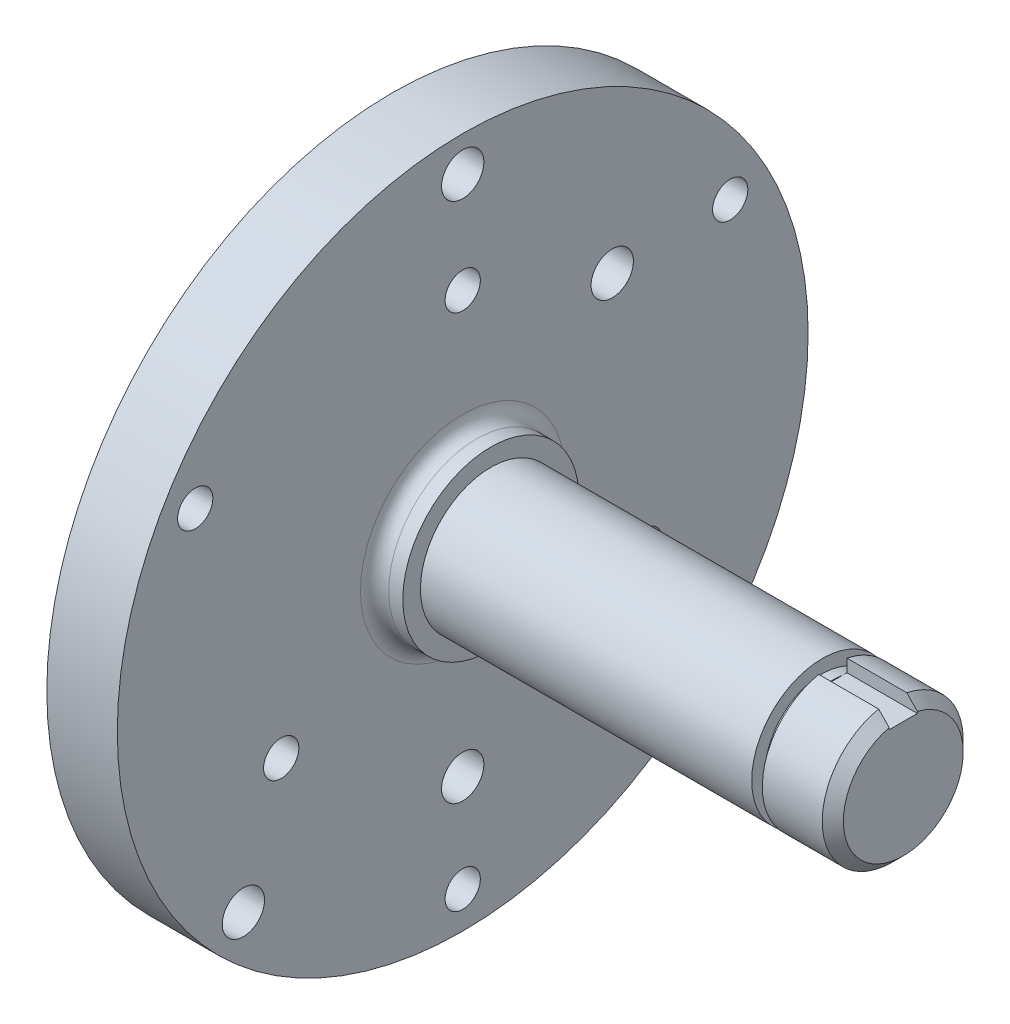
SolidWorks part; units mm, degrees
ref_plane "Plan de face" through (0, 0, 0) normal (0, 0, 1) x (1, 0, 0)
ref_plane "Plan de dessus" through (0, 0, 0) normal (0, 1, 0) x (1, 0, 0)
ref_plane "Plan de droite" through (0, 0, 0) normal (1, 0, 0) x (0, 0, -1)
sketch "Esquisse1" plane through (0, 0, 0) normal (0, 0, 1) x (1, 0, 0)
  line L0 (-18.2864, 0) -> (63.7946, 0) construction
  line L1 (-14, 0) -> (-14, 49)
  line L2 (-14, 49) -> (-4, 49)
  line L3 (-4, 49) -> (-4, 14.5)
  line L4 (-2, 12.5) -> (0, 12.5)
  line L5 (0, 12.5) -> (0, 10)
  line L6 (0, 10) -> (47, 10)
  line L7 (47, 10) -> (47, 8.1277)
  line L8 (47, 8.1277) -> (48.5, 8.1277)
  line L9 (48.5, 8.1277) -> (48.5, 10)
  line L10 (48.5, 10) -> (57, 10)
  line L11 (58.5, 8.5) -> (58.5, 0)
  line L12 (57, 10) -> (58.5, 8.5)
  line L13 (-14, 0) -> (58.5, 0)
  arc A0 (-4, 14.5) -> (-2, 12.5) centre (-2, 14.5) ccw
  point P14 (58.5, 10)
  dimension "D9" = 2
  dimension "D1" = 98
  dimension "D2" = 25
  dimension "D3" = 20
  dimension "D4" = 10
  dimension "D5" = 14
  dimension "D6" = 47
  dimension "D7" = 1.5
  dimension "D8" = 58.5
  dimension "D10" = 1.5
  dimension "D11" = 45
revolve "Révolution1" add sketch "Esquisse1" angle 360 about L0
sketch "Esquisse2" plane through (-14, 0, 0) normal (-1, 0, 0) x (0, 0, 1)
  line L0 (-51.6268, 0) -> (51.8086, 0) construction
  line L1 (0, 61.2669) -> (0, -61.2669) construction
  line L2 (0, 0) -> (-21.2132, 21.2132) construction
  line L3 (0, 0) -> (31.1127, -31.1127) construction
  circle A0 centre (0, -30) radius 3
  circle A1 centre (-21.2132, 21.2132) radius 3
  circle A2 centre (0, 44) radius 3
  circle A3 centre (31.1127, -31.1127) radius 3
  dimension "D1" = 6
  dimension "D2" = 45
  dimension "D3" = 30
  dimension "D4" = 30
  dimension "D5" = 44
  dimension "D6" = 45
  dimension "D7" = 44
  dimension "D8" = 30
extrude "Enlèv. mat.-Extru.1" cut sketch "Esquisse2" against normal up to next
hole_wizard "Trou taraudé M61" positions "Esquisse3D1" profile "Esquisse3" tap size "M6" standard "ISO" end condition through all
sketch3d "Esquisse3D1"
  point P0 (-4, 29.7321, 0)
  point P2 (-4, -43.8178, 0)
  dimension "D1" = 44
  dimension "D2" = 30
sketch "Esquisse3" plane through (-4, 29.7321, 0) normal (0, 1, 0) x (0, 0, -1)
  line L0 (0, 0) -> (0, 10)
  line L1 (0, 10) -> (2.5, 10)
  line L2 (2.5, 10) -> (2.5, 0)
  line L5 (2.5, 0) -> (0, 0)
  line L11 (0, -6.35) -> (0, 107.95) construction
  dimension "Diamètre du trou pour taraudage jusqu'au prochain" = 5
  dimension "Profondeur du trou pour taraudage jusqu'au prochain" = 10
cosmetic thread "Filetage de perçage1" parameters "D2"=6
cosmetic thread "Filetage de perçage2" parameters "D2"=6
pattern_circular "Répétition circulaire1" count 3 over 360 about axis through (0, 0, 0) along (1, 0, 0) of "Trou taraudé M61"
sketch "Esquisse4" plane through (58.5, 0, 0) normal (1, 0, 0) x (0, 0, -1)
  line L1 (-2, 12.2319) -> (2, 12.2319)
  line L2 (-2, 12.2319) -> (-2, 8)
  line L3 (-2, 8) -> (2, 8)
  line L4 (2, 12.2319) -> (2, 8)
  dimension "D1" = 8
  dimension "D2" = 4
  dimension "D3" = 2
extrude "Enlèv. mat.-Extru.4" cut sketch "Esquisse4" against normal up to surface (10 mm away) up to face at (48.5, 0, 8.1277)
